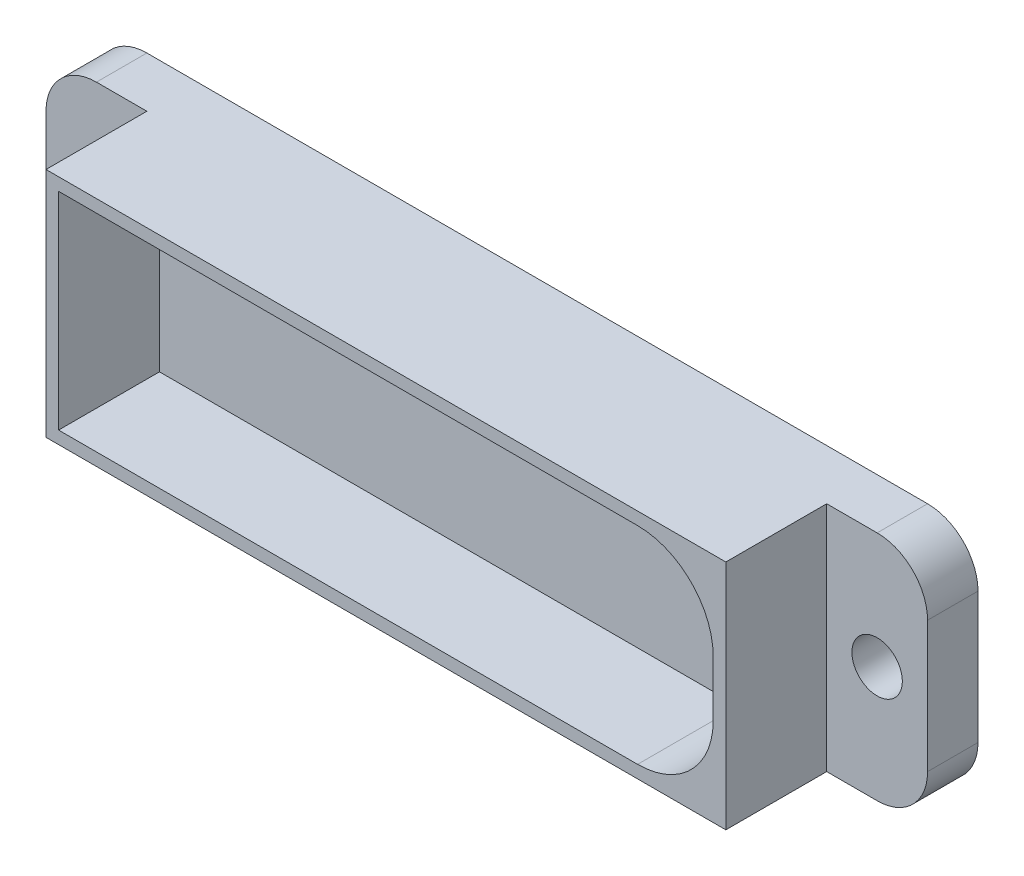
SolidWorks part; units mm, degrees
ref_plane "Front Plane" through (0, 0, 0) normal (0, 0, 1) x (1, 0, 0)
ref_plane "Top Plane" through (0, 0, 0) normal (0, 1, 0) x (1, 0, 0)
ref_plane "Right Plane" through (0, 0, 0) normal (1, 0, 0) x (0, 0, -1)
sketch "Sketch1" plane through (0, 0, 0) normal (0, 0, 1) x (1, 0, 0)
  line L0 (15.48, 0) -> (0, 0) construction
  line L1 (-15.48, -4.6) -> (15.48, -4.6)
  line L2 (-17.48, -2.6) -> (-17.48, 2.6)
  line L3 (-15.48, 4.6) -> (15.48, 4.6)
  line L4 (17.48, -2.6) -> (17.48, 2.6)
  line L5 (-17.48, -4.6) -> (17.48, 4.6) construction
  line L6 (-17.48, 4.6) -> (17.48, -4.6) construction
  line L7 (0, 0) -> (-15.48, 0) construction
  arc A0 (15.48, 4.6) -> (17.48, 2.6) centre (15.48, 2.6) cw
  arc A1 (15.48, -4.6) -> (17.48, -2.6) centre (15.48, -2.6) ccw
  arc A2 (-15.48, -4.6) -> (-17.48, -2.6) centre (-15.48, -2.6) cw
  arc A3 (-17.48, 2.6) -> (-15.48, 4.6) centre (-15.48, 2.6) cw
  circle A4 centre (-15.48, 0) radius 1
  circle A5 centre (15.48, 0) radius 1
  point P0 (0, 0)
  dimension "D3" = 2
  dimension "D4" = 2
  dimension "D1" = 34.96
  dimension "D2" = 9.2
  dimension "D5" = 30.96
extrude "Boss-Extrude1" add sketch "Sketch1" along normal blind 2
sketch "Sketch2" plane through (0, 0, 0) normal (0, 0, 1) x (1, 0, 0)
  line L0 (-15.48, -4.6) -> (15.48, -4.6) construction
  line L1 (-13.48, 4.6) -> (13.48, 4.6)
  line L2 (-13.48, 4.6) -> (-13.48, -4.6)
  line L3 (-13.48, -4.6) -> (13.48, -4.6)
  line L4 (13.48, 4.6) -> (13.48, -4.6)
  line L5 (-13.48, 4.6) -> (13.48, -4.6) construction
  line L6 (-13.48, -4.6) -> (13.48, 4.6) construction
  line L7 (-12.98, 4.1) -> (-12.98, -4.1)
  line L8 (-12.98, -4.1) -> (9.98, -4.1)
  line L9 (12.98, 1.1) -> (12.98, -1.1)
  line L10 (-12.98, 4.1) -> (9.98, 4.1)
  line L11 (-12.98, -4.1) -> (12.98, -4.1) construction
  line L12 (12.98, 4.1) -> (12.98, -4.1) construction
  line L13 (-12.98, 4.1) -> (12.98, 4.1) construction
  arc A0 (9.98, -4.1) -> (12.98, -1.1) centre (9.98, -1.1) ccw
  arc A1 (12.98, 1.1) -> (9.98, 4.1) centre (9.98, 1.1) ccw
  point P0 (0, 0)
  dimension "D3" = 3
  dimension "D1" = 26.96
  dimension "D2" = 0.5
extrude "Boss-Extrude2" add sketch "Sketch2" along normal blind 6
